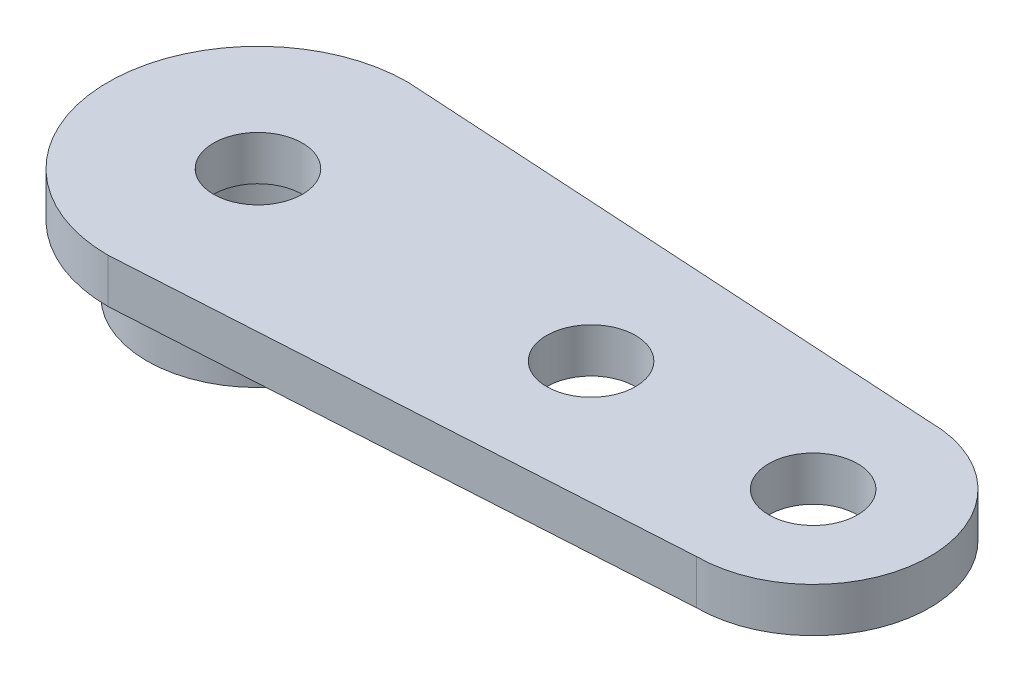
SolidWorks part; units mm, degrees
ref_plane "前视基准面" through (0, 0, 0) normal (0, 0, 1) x (1, 0, 0)
ref_plane "上视基准面" through (0, 0, 0) normal (0, 1, 0) x (1, 0, 0)
ref_plane "右视基准面" through (0, 0, 0) normal (1, 0, 0) x (0, 0, -1)
other "Configuration Table"
sketch "草图2" plane through (0, 0, 0) normal (0, 1, 0) x (1, 0, 0)
  line L0 (-86.3872, 0) -> (1, 0) construction
  line L1 (0, 3.375) -> (12.5, 2.625)
  line L2 (0, -3.375) -> (12.5, -2.625)
  line L3 (3.375, 0) -> (9.875, 0) construction
  line L4 (11.5, 0) -> (4232.9728, 0) construction
  circle A0 centre (0, 0) radius 1
  circle A1 centre (7.5, 0) radius 1
  circle A2 centre (12.5, 0) radius 1
  arc A3 (0.4035, 3.3508) -> (0.4035, -3.3508) centre (0, 0) ccw
  arc A4 (12.5, -2.625) -> (12.5, 2.625) centre (12.5, 0) ccw
  point P11 (-3.375, 0)
  point P12 (15.125, 0)
  dimension "D1" = 2
  dimension "D2" = 2
  dimension "D3" = 2
  dimension "D7" = 6.75
  dimension "D8" = 5.25
  dimension "D4" = 5
  dimension "D5" = 7.5
  dimension "D6" = 18.5
extrude "凸台-拉伸1" add sketch "草图2" along normal blind 1 contours L2 A4 L1 A3 A0 A1 A2
sketch "草图3" plane through (0, 0, 0) normal (0, 1, 0) x (1, 0, 0)
  circle A0 centre (0, 0) radius 1.75
  circle A1 centre (0, 0) radius 2.5
  dimension "D1" = 3.5
  dimension "D2" = 5
extrude "凸台-拉伸2" add sketch "草图3" against normal blind 1.5
